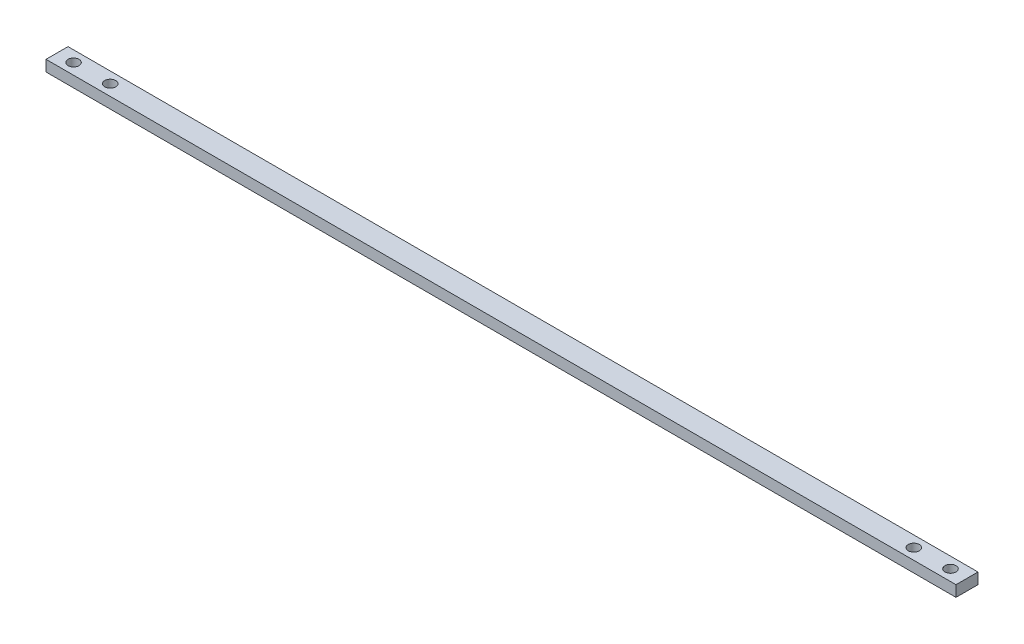
SolidWorks part; units mm, degrees
material "Gray Cast Iron (SN)"
ref_plane "Front Plane" through (0, 0, 0) normal (0, 0, 1) x (1, 0, 0)
ref_plane "Top Plane" through (0, 0, 0) normal (0, 1, 0) x (1, 0, 0)
ref_plane "Right Plane" through (0, 0, 0) normal (1, 0, 0) x (0, 0, -1)
sketch "Sketch1" plane through (0, 0, 0) normal (0, 1, 0) x (1, 0, 0)
  line L0 (0, 0) -> (0, 10.3804) construction
  line L1 (-124, -3) -> (124, -3)
  line L2 (-124, -3) -> (-124, 3)
  line L3 (-124, 3) -> (124, 3)
  line L4 (124, -3) -> (124, 3)
  line L5 (-124, -3) -> (124, 3) construction
  line L6 (-124, 3) -> (124, -3) construction
  circle A0 centre (-119.5, 0) radius 1.5
  circle A1 centre (119.5, 0) radius 1.5
  circle A2 centre (-109.5, 0) radius 1.5
  circle A3 centre (109.5, 0) radius 1.5
  point P0 (0, 0)
  dimension "D3" = 3
  dimension "D1" = 248
  dimension "D2" = 6
  dimension "D4" = 4.5
  dimension "D5" = 3
  dimension "D6" = 2
  dimension "D7" = 2
extrude "Boss-Extrude1" add sketch "Sketch1" along normal blind 3
